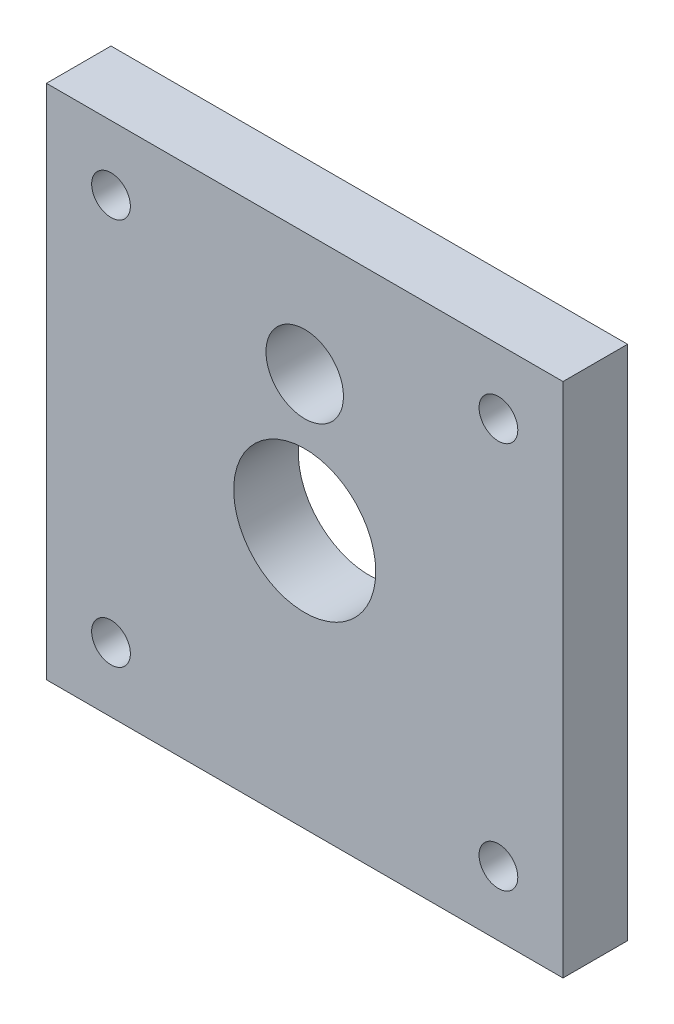
SolidWorks part; units mm, degrees
ref_plane "前视基准面" through (0, 0, 0) normal (0, 0, 1) x (1, 0, 0)
ref_plane "上视基准面" through (0, 0, 0) normal (0, 1, 0) x (1, 0, 0)
ref_plane "右视基准面" through (0, 0, 0) normal (1, 0, 0) x (0, 0, -1)
sketch "草图1" plane through (0, 0, 0) normal (0, 0, 1) x (1, 0, 0)
  line L0 (0, 0) -> (0, 33.4423) construction
  line L1 (-20, 20) -> (20, 20)
  line L2 (-20, 20) -> (-20, -20)
  line L3 (-20, -20) -> (20, -20)
  line L4 (20, 20) -> (20, -20)
  line L5 (-20, 20) -> (20, -20) construction
  line L6 (-20, -20) -> (20, 20) construction
  circle A0 centre (0, 0) radius 5.5
  circle A1 centre (0, 10.5) radius 3
  circle A2 centre (0, 10.5) radius 5.5
  circle A3 centre (-15, 15) radius 1.5
  circle A4 centre (15, 15) radius 1.5
  circle A5 centre (15, -15) radius 1.5
  circle A6 centre (-15, -15) radius 1.5
  point P20 (0, 0)
  point P21 (0, 0)
  point P22 (0, 0)
  point P23 (0, 0)
  point P25 (-12.0557, 20)
  dimension "D1" = 11
  dimension "D2" = 6
  dimension "D3" = 11
  dimension "D8" = 3
  dimension "D4" = 10.5
  dimension "D5" = 40
  dimension "D6" = 40
  dimension "D7" = 5
extrude "凸台-拉伸1" add sketch "草图1" along normal blind 5 contours L4 L1 L2 L3 A2 A0 | A0 A2 A1 | A1
